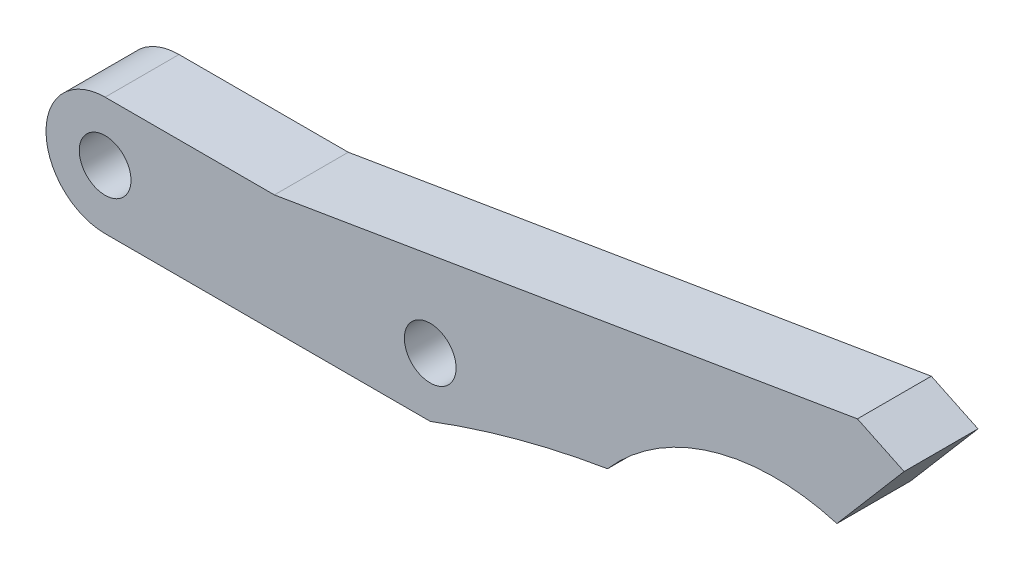
SolidWorks part; units mm, degrees
ref_plane "Front Plane" through (0, 0, 0) normal (0, 0, 1) x (1, 0, 0)
ref_plane "Top Plane" through (0, 0, 0) normal (0, 1, 0) x (1, 0, 0)
ref_plane "Right Plane" through (0, 0, 0) normal (1, 0, 0) x (0, 0, -1)
sketch "Sketch1" plane through (0, 0, 0) normal (0, 0, 1) x (1, 0, 0)
  line L0 (0, 4) -> (11.4553, 4)
  line L1 (11.4553, 4) -> (50.9067, 10.6019)
  line L2 (50.9067, 10.6019) -> (54.0658, 9.0951)
  line L3 (54.0658, 9.0951) -> (49.5196, 3.7723)
  line L5 (22, -4) -> (0, -4)
  circle A0 centre (0, 0) radius 1.75
  arc A1 (0, 4) -> (0, -4) centre (0, 0) ccw
  circle A2 centre (22, 0) radius 1.75
  arc A3 (22, -4) -> (34, -0.7766) centre (44.5247, -63.9052) cw
  arc A4 (34, -0.7766) -> (49.5196, 3.7723) centre (45.3133, -10.6259) cw
  dimension "D1" = 3.5
  dimension "D2" = 8
  dimension "D3" = 3.5
  dimension "D7" = 15
  dimension "D13" = 64
  dimension "D12" = 12
  dimension "D4" = 22
  dimension "D5" = 40
  dimension "D6" = 9.5
  dimension "D8" = 3.5
  dimension "D9" = 145
  dimension "D10" = 7
  dimension "D11" = 105
extrude "Boss-Extrude1" add sketch "Sketch1" against normal blind 5
